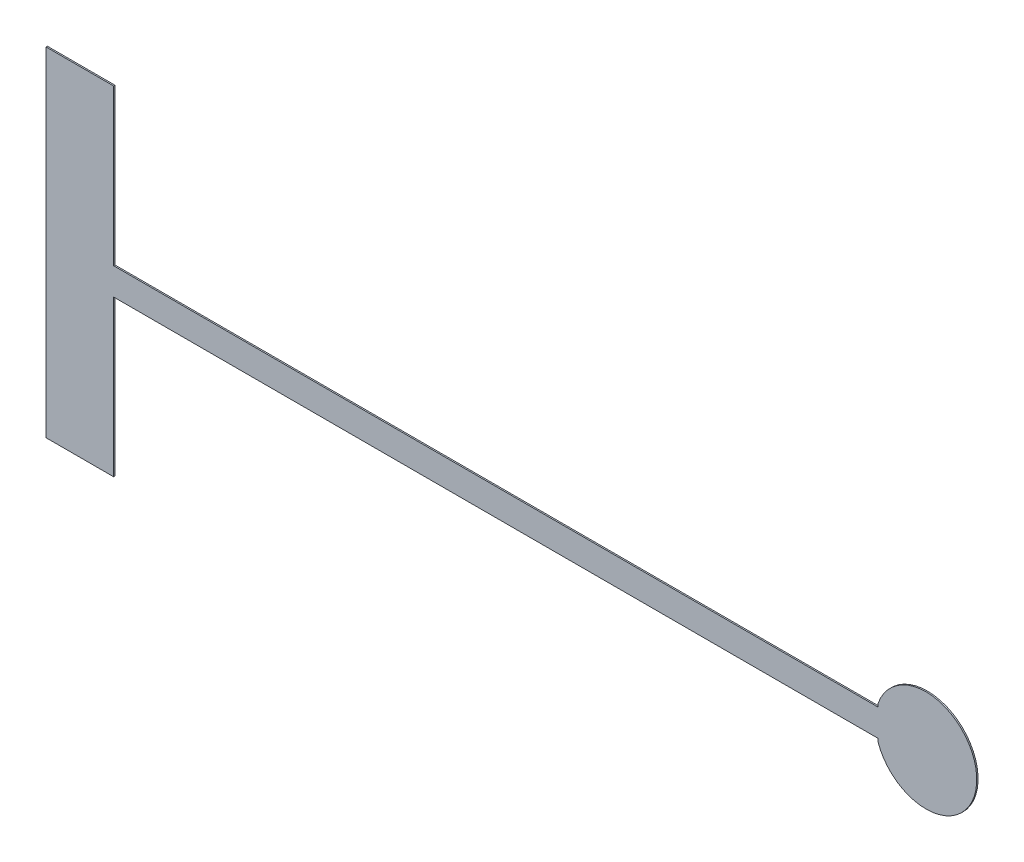
SolidWorks part; units mm, degrees
ref_plane "Front Plane" through (0, 0, 0) normal (0, 0, 1) x (1, 0, 0)
ref_plane "Top Plane" through (0, 0, 0) normal (0, 1, 0) x (1, 0, 0)
ref_plane "Right Plane" through (0, 0, 0) normal (1, 0, 0) x (0, 0, -1)
sketch "Sketch1" plane through (0, 0, 0) normal (0, 0, 1) x (1, 0, 0)
  line L0 (1000, 250) -> (5000, 250)
  line L1 (-1000, 2500) -> (1000, 2500)
  line L2 (-1000, 2500) -> (-1000, -2500)
  line L3 (-1000, -2500) -> (1000, -2500)
  line L4 (1000, 2500) -> (1000, 250)
  line L5 (-1000, 2500) -> (1000, -2500) construction
  line L6 (-1000, -2500) -> (1000, 2500) construction
  line L9 (1000, -250) -> (5000, -250)
  line L10 (5000, 250) -> (5000, 125)
  line L11 (-3000, 250) -> (5000, -250) construction
  line L12 (-3000, -250) -> (5000, 250) construction
  line L13 (5000, 125) -> (9000, 125)
  line L15 (5000, -125) -> (9000, -125)
  line L16 (9000, 125) -> (9000, 100)
  line L17 (1000, 125) -> (9000, -125) construction
  line L18 (1000, -125) -> (9000, 125) construction
  line L19 (9000, 100) -> (11256.6966, 100)
  line L21 (9000, -100) -> (11256.6966, -100)
  line L23 (6000, 100) -> (12000, -100) construction
  line L24 (6000, -100) -> (12000, 100) construction
  line L25 (1000, -250) -> (1000, -2500)
  line L26 (5000, -125) -> (5000, -250)
  line L27 (9000, -100) -> (9000, -125)
  arc A0 (11256.6966, -100) -> (11256.6966, 100) centre (12000, 0) ccw
  point P0 (0, 0)
  point P6 (1000, 0)
  point P11 (5000, 0)
  point P16 (9000, 0)
  dimension "D9" = 1500
  dimension "D1" = 2000
  dimension "D2" = 5000
  dimension "D3" = 500
  dimension "D4" = 4000
  dimension "D5" = 250
  dimension "D6" = 4000
  dimension "D7" = 200
extrude "Boss-Extrude1" add sketch "Sketch1" against normal blind 20
sketch "Sketch2" plane through (0, 0, 0) normal (0, 0, 1) x (1, 0, 0)
  line L0 (0, -11) -> (0, 11) construction
  line L1 (1000, 2500) -> (0, 2500)
  line L2 (1000, 2500) -> (1000, 250)
  line L3 (1000, 250) -> (0, 250)
  line L4 (0, 2500) -> (0, 250)
  line L5 (1000, -2500) -> (0, -2500)
  line L6 (1000, -2500) -> (1000, -250)
  line L7 (1000, -250) -> (0, -250)
  line L8 (0, -2500) -> (0, -250)
  dimension "D1" = 1000
  dimension "D2" = 2250
extrude "Cut-Extrude1" cut sketch "Sketch2" against normal through all
sketch "Sketch3" plane through (0, 0, 0) normal (0, 0, 1) x (1, 0, 0)
  line L0 (0, 0) -> (1098.3807, 0) construction
  line L1 (11, 0) -> (-11, 0) construction
  line L2 (5000, 250) -> (0, 250) construction
  line L3 (1500, 250) -> (3250, 250)
  line L4 (1500, 250) -> (1500, 200)
  line L5 (1500, 200) -> (3250, 200)
  line L7 (0, -250) -> (5000, -250) construction
  line L8 (1500, -250) -> (3250, -250)
  line L9 (1500, -250) -> (1500, -200)
  line L10 (1500, -200) -> (3250, -200)
  line L12 (0, -11) -> (0, 11) construction
  line L13 (3250, 200) -> (3250, 150)
  line L14 (3250, 250) -> (5000, 250)
  line L16 (3250, 150) -> (5000, 150)
  line L17 (5000, 250) -> (5000, 150)
  line L18 (3250, -250) -> (5000, -250)
  line L19 (3250, -200) -> (3250, -150)
  line L20 (3250, -150) -> (5000, -150)
  line L21 (5000, -250) -> (5000, -150)
  point P17 (1500, 225)
  dimension "D1" = 1098.3807
  dimension "D2" = 1750
  dimension "D3" = 50
  dimension "D4" = 1750
  dimension "D5" = 50
  dimension "D6" = 1500
  dimension "D7" = 1500
  dimension "D8" = 100
  dimension "D9" = 100
  dimension "D10" = 1750
  dimension "D11" = 1750
extrude "Cut-Extrude4" cut sketch "Sketch3" against normal through all contours L8 L18 L21 L20 L19 L10 L9
mirror "Mirror1" about plane through (0, 0, 0) normal (0, 1, 0) of "Cut-Extrude4"
sketch "Sketch5" plane through (0, 0, 0) normal (0, 0, 1) x (1, 0, 0)
  line L0 (0, -11) -> (0, 11) construction
  line L1 (0, -250) -> (11500, -250)
  line L2 (0, -250) -> (0, 250)
  line L3 (0, 250) -> (11500, 250)
  line L4 (11500, -250) -> (11500, 250)
  line L5 (0, -250) -> (1500, -250) construction
  dimension "D1" = 500
  dimension "D2" = 11500
extrude "Boss-Extrude2" add sketch "Sketch5" against normal blind 20
sketch "Sketch6" plane through (0, 0, 0) normal (0, 0, 1) x (1, 0, 0)
  line L1 (0, 250) -> (11290.9262, 250)
  line L2 (0, 250) -> (0, 200)
  line L3 (0, 200) -> (11290.9262, 200)
  line L4 (11290.9262, 250) -> (11290.9262, 200)
  dimension "D1" = 50
extrude "Cut-Extrude5" cut sketch "Sketch6" against normal through all
mirror "Mirror2" about plane through (0, 0, 0) normal (0, 1, 0) of "Cut-Extrude5"
